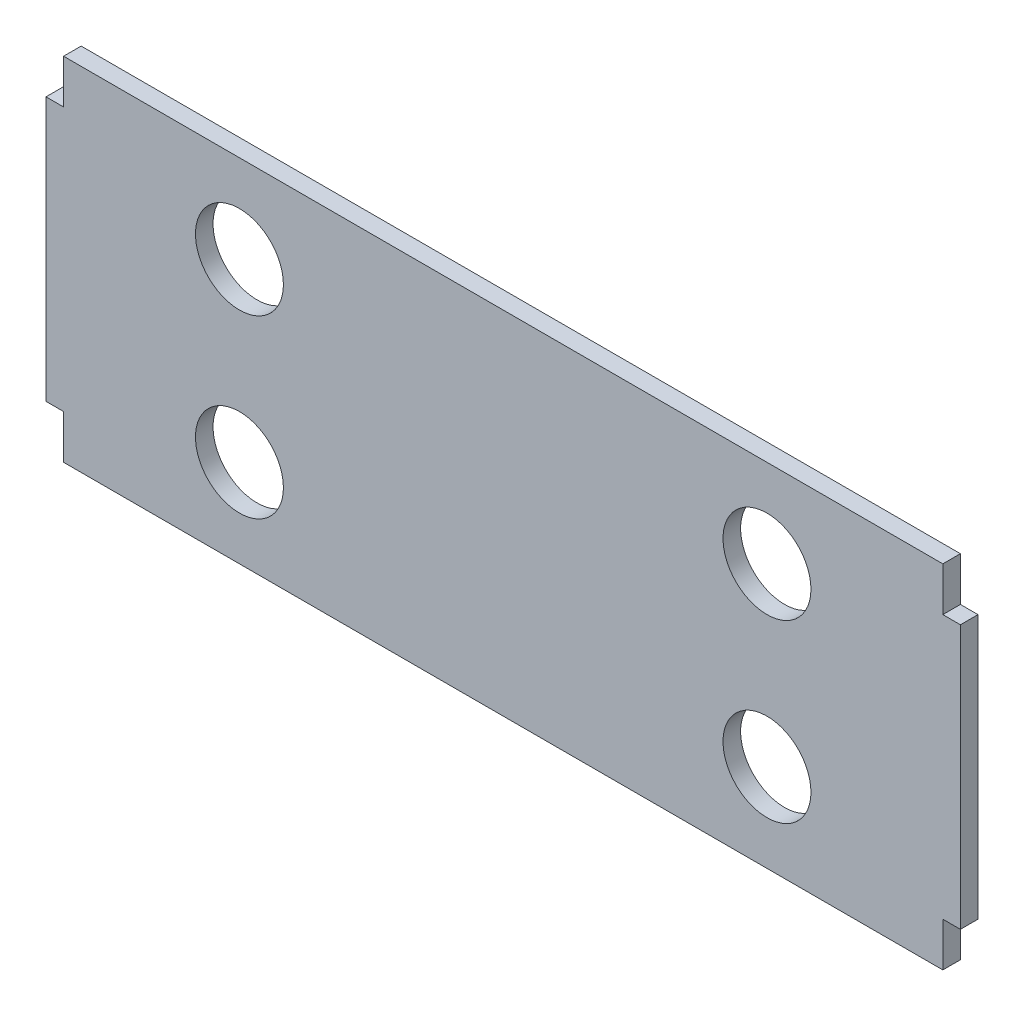
SolidWorks part; units mm, degrees
ref_plane "前视基准面" through (0, 0, 0) normal (0, 0, 1) x (1, 0, 0)
ref_plane "上视基准面" through (0, 0, 0) normal (0, 1, 0) x (1, 0, 0)
ref_plane "右视基准面" through (0, 0, 0) normal (1, 0, 0) x (0, 0, -1)
sketch "草图1" plane through (0, 0, 0) normal (0, 0, 1) x (1, 0, 0)
  line L0 (0, 0) -> (0, 40)
  line L1 (0, 0) -> (100, 0)
  line L2 (0, 40) -> (100, 40)
  line L3 (100, 0) -> (100, 40)
  line L4 (0, 35) -> (-2, 35)
  line L5 (0, 35) -> (0, 5)
  line L6 (-2, 35) -> (-2, 5)
  line L7 (0, 5) -> (-2, 5)
  line L8 (100, 35) -> (102, 35)
  line L9 (100, 35) -> (100, 5)
  line L10 (102, 35) -> (102, 5)
  line L11 (100, 5) -> (102, 5)
extrude "凸台-拉伸1" add sketch "草图1" along normal blind 2 contours L7 L0 L4 L6 | L1 L3 L2 L0 | L3 L11 L10 L8
sketch "草图2" plane through (0, 0, 0) normal (0, 0, 1) x (1, 0, 0)
  circle A0 centre (20, 30) radius 5
  circle A1 centre (20, 10) radius 5
  circle A2 centre (80, 30) radius 5
  circle A3 centre (80, 10) radius 5
  point P4 (0, 0)
  point P7 (0, 0)
  point P10 (0, 0)
extrude "切除-拉伸1" cut sketch "草图2" along normal through all contours A0 | A2 | A3 | A1
